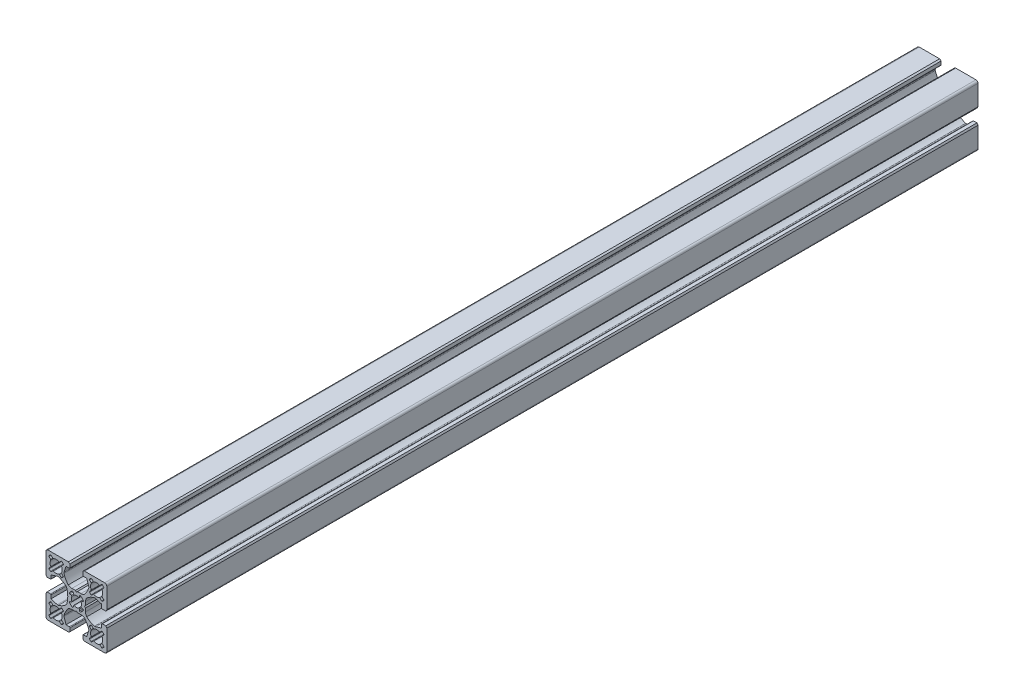
SolidWorks part; units mm, degrees
ref_plane "정면" through (0, 0, 0) normal (0, 0, 1) x (1, 0, 0)
ref_plane "윗면" through (0, 0, 0) normal (0, 1, 0) x (1, 0, 0)
ref_plane "우측면" through (0, 0, 0) normal (1, 0, 0) x (0, 0, -1)
sketch "Model" plane through (0, 0, 0) normal (0, 0, 1) x (1, 0, 0)
  line L0 (465.6218, 205.5838) -> (465.6218, 209.9838) construction
  line L1 (463.4218, 207.7838) -> (467.8218, 207.7838) construction
  line L2 (462.8793, 206.102) -> (462.1388, 205.3614)
  line L3 (463.1994, 204.3007) -> (463.94, 205.0413)
  line L4 (467.3037, 205.0413) -> (468.0443, 204.3007)
  line L5 (469.1049, 205.3614) -> (468.3643, 206.102)
  line L6 (468.3643, 209.4657) -> (469.1049, 210.2063)
  line L7 (468.0443, 211.2669) -> (467.3037, 210.5263)
  line L8 (463.94, 210.5263) -> (463.1994, 211.2669)
  line L9 (462.1388, 210.2063) -> (462.8793, 209.4657)
  line L10 (463.4211, 187.7832) -> (467.8211, 187.7829) construction
  line L11 (465.6212, 189.9831) -> (465.6209, 185.5831) construction
  line L12 (462.8787, 189.4651) -> (462.1382, 190.2057)
  line L13 (463.1989, 191.2663) -> (463.9394, 190.5257)
  line L14 (467.3031, 190.5254) -> (468.0438, 191.2659)
  line L15 (469.1043, 190.2052) -> (468.3637, 189.4647)
  line L16 (468.3634, 186.101) -> (469.1039, 185.3604)
  line L17 (468.0432, 184.2998) -> (467.3027, 185.0404)
  line L18 (463.939, 185.0407) -> (463.1984, 184.3002)
  line L19 (462.1378, 185.3609) -> (462.8784, 186.1014)
  line L20 (448.3673, 189.4651) -> (449.1078, 190.2057)
  line L21 (448.0471, 191.2663) -> (447.3066, 190.5257)
  line L22 (443.9429, 190.5254) -> (443.2023, 191.2659)
  line L23 (442.1417, 190.2052) -> (442.8823, 189.4647)
  line L24 (442.8826, 186.101) -> (442.1421, 185.3604)
  line L25 (443.2028, 184.2998) -> (443.9433, 185.0404)
  line L26 (447.307, 185.0407) -> (448.0476, 184.3002)
  line L27 (449.1082, 185.3609) -> (448.3676, 186.1014)
  line L28 (445.6248, 189.9831) -> (445.6251, 185.5831) construction
  line L29 (447.825, 187.7832) -> (443.425, 187.7829) construction
  line L30 (447.8242, 207.7838) -> (443.4242, 207.7838) construction
  line L31 (445.6242, 205.5838) -> (445.6242, 209.9838) construction
  line L32 (471.0819, 197.7838) -> (439.4, 197.7838) construction
  line L33 (455.6242, 181.8427) -> (455.6242, 213.7801) construction
  line L34 (457.2103, 201.0212) -> (457.0767, 200.2802)
  line L35 (454.1716, 200.2802) -> (454.0381, 201.0212)
  line L36 (452.3868, 199.37) -> (453.1278, 199.2364)
  line L37 (453.1278, 196.3313) -> (452.3868, 196.1977)
  line L38 (454.0381, 194.5465) -> (454.1716, 195.2874)
  line L39 (457.0767, 195.2874) -> (457.2103, 194.5465)
  line L40 (458.8615, 196.1977) -> (458.1206, 196.3313)
  line L41 (458.1206, 199.2364) -> (458.8615, 199.37)
  line L42 (448.3667, 206.102) -> (449.1073, 205.3614)
  line L43 (448.0466, 204.3007) -> (447.306, 205.0413)
  line L44 (443.9423, 205.0413) -> (443.2018, 204.3007)
  line L45 (442.1411, 205.3614) -> (442.8817, 206.102)
  line L46 (442.8817, 209.4657) -> (442.1411, 210.2063)
  line L47 (443.2018, 211.2669) -> (443.9423, 210.5263)
  line L48 (447.306, 210.5263) -> (448.0466, 211.2669)
  line L49 (449.1073, 210.2063) -> (448.3667, 209.4657)
  line L50 (459.5742, 182.7838) -> (458.7742, 183.2838)
  line L51 (458.7742, 183.2838) -> (458.7742, 184.9838)
  line L52 (459.0742, 185.2838) -> (460.7242, 185.2838)
  line L53 (460.7242, 185.2838) -> (461.7118, 188.3356)
  line L54 (457.842, 193.2838) -> (456.1242, 193.2838)
  line L55 (456.1242, 193.2838) -> (455.6242, 193.7838)
  line L56 (455.6242, 193.7838) -> (455.1242, 193.2838)
  line L57 (455.1242, 193.2838) -> (453.4063, 193.2838)
  line L58 (449.5366, 188.3356) -> (450.5242, 185.2838)
  line L59 (450.5242, 185.2838) -> (452.1742, 185.2838)
  line L60 (452.4742, 184.9838) -> (452.4742, 183.2838)
  line L61 (452.4742, 183.2838) -> (451.6742, 182.7838)
  line L62 (451.6742, 182.7838) -> (441.6242, 182.7838)
  line L63 (440.6242, 183.7838) -> (440.6242, 193.8338)
  line L64 (440.6242, 193.8338) -> (441.1242, 194.6338)
  line L65 (441.1242, 194.6338) -> (442.8242, 194.6338)
  line L66 (443.1242, 194.3338) -> (443.1242, 192.6838)
  line L67 (443.1242, 192.6838) -> (446.1759, 191.6962)
  line L68 (451.1242, 195.566) -> (451.1242, 197.2838)
  line L69 (451.1242, 197.2838) -> (451.6242, 197.7838)
  line L70 (451.6242, 197.7838) -> (451.1242, 198.2838)
  line L71 (451.1242, 198.2838) -> (451.1242, 200.0017)
  line L72 (446.1759, 203.8714) -> (443.1242, 202.8838)
  line L73 (443.1242, 202.8838) -> (443.1242, 201.2338)
  line L74 (442.8242, 200.9338) -> (441.1242, 200.9338)
  line L75 (441.1242, 200.9338) -> (440.6242, 201.7338)
  line L76 (440.6242, 201.7338) -> (440.6242, 211.7838)
  line L77 (441.6242, 212.7838) -> (451.6742, 212.7838)
  line L78 (451.6742, 212.7838) -> (452.4742, 212.2838)
  line L79 (452.4742, 212.2838) -> (452.4742, 210.5838)
  line L80 (452.1742, 210.2838) -> (450.5242, 210.2838)
  line L81 (450.5242, 210.2838) -> (449.5366, 207.2321)
  line L82 (453.4063, 202.2838) -> (455.1242, 202.2838)
  line L83 (455.1242, 202.2838) -> (455.6242, 201.7838)
  line L84 (455.6242, 201.7838) -> (456.1242, 202.2838)
  line L85 (456.1242, 202.2838) -> (457.842, 202.2838)
  line L86 (461.7118, 207.2321) -> (460.7242, 210.2838)
  line L87 (460.7242, 210.2838) -> (459.0742, 210.2838)
  line L88 (458.7742, 210.5838) -> (458.7742, 212.2838)
  line L89 (458.7742, 212.2838) -> (459.5742, 212.7838)
  line L90 (459.5742, 212.7838) -> (469.6242, 212.7838)
  line L91 (470.6242, 211.7838) -> (470.6242, 201.7338)
  line L92 (470.6242, 201.7338) -> (470.1242, 200.9338)
  line L93 (470.1242, 200.9338) -> (468.4242, 200.9338)
  line L94 (468.1242, 201.2338) -> (468.1242, 202.8838)
  line L95 (468.1242, 202.8838) -> (465.0724, 203.8714)
  line L96 (460.1242, 200.0017) -> (460.1242, 198.2838)
  line L97 (460.1242, 198.2838) -> (459.6242, 197.7838)
  line L98 (459.6242, 197.7838) -> (460.1242, 197.2838)
  line L99 (460.1242, 197.2838) -> (460.1242, 195.566)
  line L100 (465.0724, 191.6962) -> (468.1242, 192.6838)
  line L101 (468.1242, 192.6838) -> (468.1242, 194.3338)
  line L102 (468.4242, 194.6338) -> (470.1242, 194.6338)
  line L103 (470.1242, 194.6338) -> (470.6242, 193.8338)
  line L104 (470.6242, 193.8338) -> (470.6242, 183.7838)
  line L105 (469.6242, 182.7838) -> (459.5742, 182.7838)
  arc A0 (462.8793, 206.102) -> (462.9358, 206.4477) centre (462.6672, 206.3141) ccw
  arc A1 (462.1388, 205.3614) -> (462.1172, 204.9611) centre (462.3509, 205.1493) ccw
  arc A2 (462.1172, 204.9611) -> (462.7991, 204.2792) centre (465.6218, 207.7838) ccw
  arc A3 (462.7991, 204.2792) -> (463.1994, 204.3007) centre (462.9873, 204.5129) ccw
  arc A4 (464.2857, 205.0978) -> (463.94, 205.0413) centre (464.1521, 204.8292) ccw
  arc A5 (464.2857, 205.0978) -> (466.9579, 205.0978) centre (465.6218, 207.7838) ccw
  arc A6 (467.3037, 205.0413) -> (466.9579, 205.0978) centre (467.0916, 204.8292) ccw
  arc A7 (468.0443, 204.3007) -> (468.4446, 204.2792) centre (468.2564, 204.5129) ccw
  arc A8 (468.4446, 204.2792) -> (469.1264, 204.9611) centre (465.6218, 207.7838) ccw
  arc A9 (469.1264, 204.9611) -> (469.1049, 205.3614) centre (468.8928, 205.1493) ccw
  arc A10 (468.3079, 206.4477) -> (468.3643, 206.102) centre (468.5765, 206.3141) ccw
  arc A11 (468.3079, 206.4477) -> (468.3079, 209.1199) centre (465.6218, 207.7838) ccw
  arc A12 (468.3643, 209.4657) -> (468.3079, 209.1199) centre (468.5765, 209.2536) ccw
  arc A13 (469.1049, 210.2063) -> (469.1264, 210.6066) centre (468.8928, 210.4184) ccw
  arc A14 (469.1264, 210.6066) -> (468.4446, 211.2884) centre (465.6218, 207.7838) ccw
  arc A15 (468.4446, 211.2884) -> (468.0443, 211.2669) centre (468.2564, 211.0548) ccw
  arc A16 (466.9579, 210.4699) -> (467.3037, 210.5263) centre (467.0916, 210.7385) ccw
  arc A17 (466.9579, 210.4699) -> (464.2857, 210.4699) centre (465.6218, 207.7838) ccw
  arc A18 (463.94, 210.5263) -> (464.2857, 210.4699) centre (464.1521, 210.7385) ccw
  arc A19 (463.1994, 211.2669) -> (462.7991, 211.2884) centre (462.9873, 211.0548) ccw
  arc A20 (462.7991, 211.2884) -> (462.1172, 210.6066) centre (465.6218, 207.7838) ccw
  arc A21 (462.1172, 210.6066) -> (462.1388, 210.2063) centre (462.3509, 210.4184) ccw
  arc A22 (462.9358, 209.1199) -> (462.8793, 209.4657) centre (462.6672, 209.2536) ccw
  arc A23 (462.9358, 209.1199) -> (462.9358, 206.4477) centre (465.6218, 207.7838) ccw
  arc A24 (462.9351, 189.1194) -> (462.8787, 189.4651) centre (462.6665, 189.253) ccw
  arc A25 (462.1167, 190.6061) -> (462.1382, 190.2057) centre (462.3503, 190.4179) ccw
  arc A26 (462.7986, 191.2879) -> (462.1167, 190.6061) centre (465.6211, 187.7831) ccw
  arc A27 (463.1989, 191.2663) -> (462.7986, 191.2879) centre (462.9868, 191.0542) ccw
  arc A28 (463.9394, 190.5257) -> (464.2852, 190.4692) centre (464.1516, 190.7378) ccw
  arc A29 (466.9574, 190.469) -> (464.2852, 190.4692) centre (465.6211, 187.7831) ccw
  arc A30 (466.9574, 190.469) -> (467.3031, 190.5254) centre (467.091, 190.7376) ccw
  arc A31 (468.4441, 191.2874) -> (468.0438, 191.2659) centre (468.2559, 191.0538) ccw
  arc A32 (469.1259, 190.6055) -> (468.4441, 191.2874) centre (465.6211, 187.7831) ccw
  arc A33 (469.1043, 190.2052) -> (469.1259, 190.6055) centre (468.8922, 190.4174) ccw
  arc A34 (468.3637, 189.4647) -> (468.3072, 189.119) centre (468.5758, 189.2525) ccw
  arc A35 (468.307, 186.4467) -> (468.3072, 189.119) centre (465.6211, 187.7831) ccw
  arc A36 (468.307, 186.4467) -> (468.3634, 186.101) centre (468.5756, 186.3131) ccw
  arc A37 (469.1254, 184.96) -> (469.1039, 185.3604) centre (468.8918, 185.1482) ccw
  arc A38 (468.4435, 184.2782) -> (469.1254, 184.96) centre (465.6211, 187.7831) ccw
  arc A39 (468.0432, 184.2998) -> (468.4435, 184.2782) centre (468.2554, 184.5119) ccw
  arc A40 (467.3027, 185.0404) -> (466.957, 185.0969) centre (467.0905, 184.8283) ccw
  arc A41 (464.2847, 185.0971) -> (466.957, 185.0969) centre (465.6211, 187.7831) ccw
  arc A42 (464.2847, 185.0971) -> (463.939, 185.0407) centre (464.1511, 184.8285) ccw
  arc A43 (462.798, 184.2787) -> (463.1984, 184.3002) centre (462.9862, 184.5123) ccw
  arc A44 (462.1162, 184.9606) -> (462.798, 184.2787) centre (465.6211, 187.7831) ccw
  arc A45 (462.1378, 185.3609) -> (462.1162, 184.9606) centre (462.3499, 185.1488) ccw
  arc A46 (462.8784, 186.1014) -> (462.9349, 186.4472) centre (462.6663, 186.3136) ccw
  arc A47 (462.9351, 189.1194) -> (462.9349, 186.4472) centre (465.6211, 187.7831) ccw
  arc A48 (448.3673, 189.4651) -> (448.3109, 189.1194) centre (448.5795, 189.253) ccw
  arc A49 (449.1078, 190.2057) -> (449.1293, 190.6061) centre (448.8957, 190.4179) ccw
  arc A50 (449.1293, 190.6061) -> (448.4474, 191.2879) centre (445.625, 187.7831) ccw
  arc A51 (448.4474, 191.2879) -> (448.0471, 191.2663) centre (448.2593, 191.0542) ccw
  arc A52 (446.9609, 190.4692) -> (447.3066, 190.5257) centre (447.0944, 190.7378) ccw
  arc A53 (446.9609, 190.4692) -> (444.2886, 190.469) centre (445.625, 187.7831) ccw
  arc A54 (443.9429, 190.5254) -> (444.2886, 190.469) centre (444.155, 190.7376) ccw
  arc A55 (443.2023, 191.2659) -> (442.8019, 191.2874) centre (442.9901, 191.0538) ccw
  arc A56 (442.8019, 191.2874) -> (442.1201, 190.6055) centre (445.625, 187.7831) ccw
  arc A57 (442.1201, 190.6055) -> (442.1417, 190.2052) centre (442.3538, 190.4174) ccw
  arc A58 (442.9388, 189.119) -> (442.8823, 189.4647) centre (442.6702, 189.2525) ccw
  arc A59 (442.9388, 189.119) -> (442.939, 186.4467) centre (445.625, 187.7831) ccw
  arc A60 (442.8826, 186.101) -> (442.939, 186.4467) centre (442.6704, 186.3131) ccw
  arc A61 (442.1421, 185.3604) -> (442.1206, 184.96) centre (442.3542, 185.1482) ccw
  arc A62 (442.1206, 184.96) -> (442.8025, 184.2782) centre (445.625, 187.7831) ccw
  arc A63 (442.8025, 184.2782) -> (443.2028, 184.2998) centre (442.9907, 184.5119) ccw
  arc A64 (444.2891, 185.0969) -> (443.9433, 185.0404) centre (444.1555, 184.8283) ccw
  arc A65 (444.2891, 185.0969) -> (446.9613, 185.0971) centre (445.625, 187.7831) ccw
  arc A66 (447.307, 185.0407) -> (446.9613, 185.0971) centre (447.0949, 184.8285) ccw
  arc A67 (448.0476, 184.3002) -> (448.448, 184.2787) centre (448.2598, 184.5123) ccw
  arc A68 (448.448, 184.2787) -> (449.1298, 184.9606) centre (445.625, 187.7831) ccw
  arc A69 (449.1298, 184.9606) -> (449.1082, 185.3609) centre (448.8961, 185.1488) ccw
  arc A70 (448.3111, 186.4472) -> (448.3676, 186.1014) centre (448.5797, 186.3136) ccw
  arc A71 (448.3111, 186.4472) -> (448.3109, 189.1194) centre (445.625, 187.7831) ccw
  arc A72 (458.8615, 199.37) -> (459.0666, 199.8178) centre (458.8083, 199.6652) ccw
  arc A73 (459.0666, 199.8178) -> (457.6582, 201.2262) centre (455.623, 197.7827) ccw
  arc A74 (457.6582, 201.2262) -> (457.2103, 201.0212) centre (457.5055, 200.9679) ccw
  arc A75 (456.6575, 200.0603) -> (457.0767, 200.2802) centre (456.7815, 200.3335) ccw
  arc A76 (456.6575, 200.0603) -> (454.5909, 200.0603) centre (455.6242, 197.7838) ccw
  arc A77 (454.1716, 200.2802) -> (454.5909, 200.0603) centre (454.4669, 200.3335) ccw
  arc A78 (454.0381, 201.0212) -> (453.5902, 201.2262) centre (453.7428, 200.9679) ccw
  arc A79 (453.5902, 201.2262) -> (452.1818, 199.8178) centre (455.6253, 197.7827) ccw
  arc A80 (452.1818, 199.8178) -> (452.3868, 199.37) centre (452.4401, 199.6652) ccw
  arc A81 (453.3477, 198.8171) -> (453.1278, 199.2364) centre (453.0745, 198.9411) ccw
  arc A82 (453.3477, 198.8171) -> (453.3477, 196.7505) centre (455.6242, 197.7838) ccw
  arc A83 (453.1278, 196.3313) -> (453.3477, 196.7505) centre (453.0745, 196.6265) ccw
  arc A84 (452.3868, 196.1977) -> (452.1818, 195.7498) centre (452.4401, 195.9025) ccw
  arc A85 (452.1818, 195.7498) -> (453.5902, 194.3414) centre (455.6253, 197.785) ccw
  arc A86 (453.5902, 194.3414) -> (454.0381, 194.5465) centre (453.7428, 194.5997) ccw
  arc A87 (454.5909, 195.5074) -> (454.1716, 195.2874) centre (454.4669, 195.2342) ccw
  arc A88 (454.5909, 195.5074) -> (456.6575, 195.5074) centre (455.6242, 197.7838) ccw
  arc A89 (457.0767, 195.2874) -> (456.6575, 195.5074) centre (456.7815, 195.2342) ccw
  arc A90 (457.2103, 194.5465) -> (457.6582, 194.3414) centre (457.5055, 194.5997) ccw
  arc A91 (457.6582, 194.3414) -> (459.0666, 195.7498) centre (455.623, 197.785) ccw
  arc A92 (459.0666, 195.7498) -> (458.8615, 196.1977) centre (458.8083, 195.9025) ccw
  arc A93 (457.9006, 196.7505) -> (458.1206, 196.3313) centre (458.1738, 196.6265) ccw
  arc A94 (457.9006, 196.7505) -> (457.9006, 198.8171) centre (455.6242, 197.7838) ccw
  arc A95 (458.1206, 199.2364) -> (457.9006, 198.8171) centre (458.1738, 198.9411) ccw
  arc A96 (448.3102, 206.4477) -> (448.3667, 206.102) centre (448.5788, 206.3141) ccw
  arc A97 (449.1288, 204.9611) -> (449.1073, 205.3614) centre (448.8951, 205.1493) ccw
  arc A98 (448.4469, 204.2792) -> (449.1288, 204.9611) centre (445.6242, 207.7838) ccw
  arc A99 (448.0466, 204.3007) -> (448.4469, 204.2792) centre (448.2587, 204.5129) ccw
  arc A100 (447.306, 205.0413) -> (446.9603, 205.0978) centre (447.0939, 204.8292) ccw
  arc A101 (444.2881, 205.0978) -> (446.9603, 205.0978) centre (445.6242, 207.7838) ccw
  arc A102 (444.2881, 205.0978) -> (443.9423, 205.0413) centre (444.1545, 204.8292) ccw
  arc A103 (442.8014, 204.2792) -> (443.2018, 204.3007) centre (442.9896, 204.5129) ccw
  arc A104 (442.1196, 204.9611) -> (442.8014, 204.2792) centre (445.6242, 207.7838) ccw
  arc A105 (442.1411, 205.3614) -> (442.1196, 204.9611) centre (442.3532, 205.1493) ccw
  arc A106 (442.8817, 206.102) -> (442.9381, 206.4477) centre (442.6695, 206.3141) ccw
  arc A107 (442.9381, 209.1199) -> (442.9381, 206.4477) centre (445.6242, 207.7838) ccw
  arc A108 (442.9381, 209.1199) -> (442.8817, 209.4657) centre (442.6695, 209.2536) ccw
  arc A109 (442.1196, 210.6066) -> (442.1411, 210.2063) centre (442.3532, 210.4184) ccw
  arc A110 (442.8014, 211.2884) -> (442.1196, 210.6066) centre (445.6242, 207.7838) ccw
  arc A111 (443.2018, 211.2669) -> (442.8014, 211.2884) centre (442.9896, 211.0548) ccw
  arc A112 (443.9423, 210.5263) -> (444.2881, 210.4699) centre (444.1545, 210.7385) ccw
  arc A113 (446.9603, 210.4699) -> (444.2881, 210.4699) centre (445.6242, 207.7838) ccw
  arc A114 (446.9603, 210.4699) -> (447.306, 210.5263) centre (447.0939, 210.7385) ccw
  arc A115 (448.4469, 211.2884) -> (448.0466, 211.2669) centre (448.2587, 211.0548) ccw
  arc A116 (449.1288, 210.6066) -> (448.4469, 211.2884) centre (445.6242, 207.7838) ccw
  arc A117 (449.1073, 210.2063) -> (449.1288, 210.6066) centre (448.8951, 210.4184) ccw
  arc A118 (448.3667, 209.4657) -> (448.3102, 209.1199) centre (448.5788, 209.2536) ccw
  arc A119 (448.3102, 206.4477) -> (448.3102, 209.1199) centre (445.6242, 207.7838) ccw
  arc A120 (459.0742, 185.2838) -> (458.7742, 184.9838) centre (459.0742, 184.9838) ccw
  arc A121 (461.7118, 188.3356) -> (461.7375, 188.856) centre (460.7604, 188.6435) ccw
  arc A122 (461.7375, 188.856) -> (459.6282, 192.6941) centre (452.2648, 186.1487) ccw
  arc A123 (459.6282, 192.6941) -> (457.842, 193.2838) centre (457.842, 190.2838) ccw
  arc A124 (453.4063, 193.2838) -> (451.6202, 192.6941) centre (453.4063, 190.2838) ccw
  arc A125 (451.6202, 192.6941) -> (449.5108, 188.856) centre (458.9836, 186.1487) ccw
  arc A126 (449.5108, 188.856) -> (449.5366, 188.3356) centre (450.488, 188.6435) ccw
  arc A127 (452.4742, 184.9838) -> (452.1742, 185.2838) centre (452.1742, 184.9838) ccw
  arc A128 (440.6242, 183.7838) -> (441.6242, 182.7838) centre (441.6242, 183.7838) ccw
  arc A129 (443.1242, 194.3338) -> (442.8242, 194.6338) centre (442.8242, 194.3338) ccw
  arc A130 (446.1759, 191.6962) -> (446.6963, 191.6705) centre (446.4838, 192.6476) ccw
  arc A131 (446.6963, 191.6705) -> (450.5345, 193.7798) centre (443.9891, 201.1432) ccw
  arc A132 (450.5345, 193.7798) -> (451.1242, 195.566) centre (448.1242, 195.566) ccw
  arc A133 (451.1242, 200.0017) -> (450.5345, 201.7878) centre (448.1242, 200.0017) ccw
  arc A134 (450.5345, 201.7878) -> (446.6963, 203.8972) centre (443.9891, 194.4244) ccw
  arc A135 (446.6963, 203.8972) -> (446.1759, 203.8714) centre (446.4838, 202.92) ccw
  arc A136 (442.8242, 200.9338) -> (443.1242, 201.2338) centre (442.8242, 201.2338) ccw
  arc A137 (441.6242, 212.7838) -> (440.6242, 211.7838) centre (441.6242, 211.7838) ccw
  arc A138 (452.1742, 210.2838) -> (452.4742, 210.5838) centre (452.1742, 210.5838) ccw
  arc A139 (449.5366, 207.2321) -> (449.5108, 206.7117) centre (450.488, 206.9242) ccw
  arc A140 (449.5108, 206.7117) -> (451.6202, 202.8735) centre (458.9836, 209.4189) ccw
  arc A141 (451.6202, 202.8735) -> (453.4063, 202.2838) centre (453.4063, 205.2838) ccw
  arc A142 (457.842, 202.2838) -> (459.6282, 202.8735) centre (457.842, 205.2838) ccw
  arc A143 (459.6282, 202.8735) -> (461.7375, 206.7117) centre (452.2648, 209.4189) ccw
  arc A144 (461.7375, 206.7117) -> (461.7118, 207.2321) centre (460.7604, 206.9242) ccw
  arc A145 (458.7742, 210.5838) -> (459.0742, 210.2838) centre (459.0742, 210.5838) ccw
  arc A146 (470.6242, 211.7838) -> (469.6242, 212.7838) centre (469.6242, 211.7838) ccw
  arc A147 (468.1242, 201.2338) -> (468.4242, 200.9338) centre (468.4242, 201.2338) ccw
  arc A148 (465.0724, 203.8714) -> (464.552, 203.8972) centre (464.7645, 202.92) ccw
  arc A149 (464.552, 203.8972) -> (460.7139, 201.7878) centre (467.2593, 194.4244) ccw
  arc A150 (460.7139, 201.7878) -> (460.1242, 200.0017) centre (463.1242, 200.0017) ccw
  arc A151 (460.1242, 195.566) -> (460.7139, 193.7798) centre (463.1242, 195.566) ccw
  arc A152 (460.7139, 193.7798) -> (464.552, 191.6705) centre (467.2593, 201.1432) ccw
  arc A153 (464.552, 191.6705) -> (465.0724, 191.6962) centre (464.7645, 192.6476) ccw
  arc A154 (468.4242, 194.6338) -> (468.1242, 194.3338) centre (468.4242, 194.3338) ccw
  arc A155 (469.6242, 182.7838) -> (470.6242, 183.7838) centre (469.6242, 183.7838) ccw
  dimension "D1" = 30
  dimension "D2" = 30
  dimension "D3" = 15
  dimension "D4" = 15
extrude "보스-돌출1" add sketch "Model" along normal blind 430
